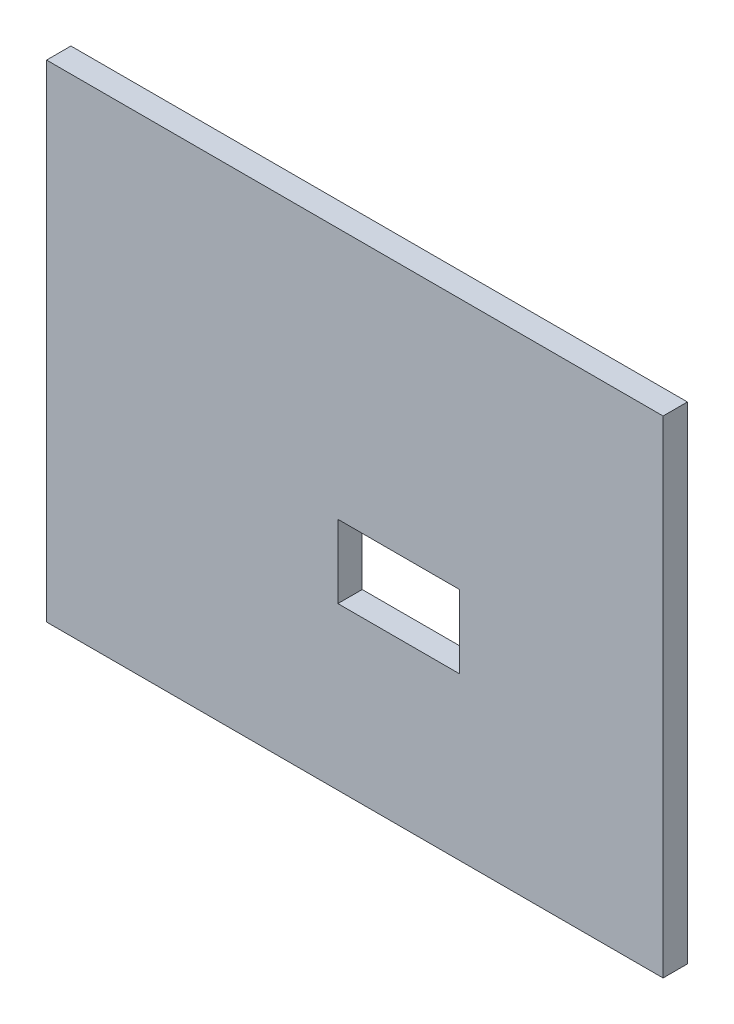
SolidWorks part; units mm, degrees
ref_plane "Front Plane" through (0, 0, 0) normal (0, 0, 1) x (1, 0, 0)
ref_plane "Top Plane" through (0, 0, 0) normal (0, 1, 0) x (1, 0, 0)
ref_plane "Right Plane" through (0, 0, 0) normal (1, 0, 0) x (0, 0, -1)
sketch "Sketch1" plane through (0, 0, 0) normal (0, 0, 1) x (1, 0, 0)
  line L1 (-38, 30) -> (38, 30)
  line L2 (-38, 30) -> (-38, -30)
  line L3 (-38, -30) -> (38, -30)
  line L4 (38, 30) -> (38, -30)
  line L5 (-38, 30) -> (38, -30) construction
  line L6 (-38, -30) -> (38, 30) construction
  point P0 (0, 0)
  dimension "D1" = 76
  dimension "D2" = 60
extrude "Boss-Extrude1" add sketch "Sketch1" along normal blind 3
sketch "Sketch2" plane through (0, 0, 3) normal (0, 0, 1) x (1, 0, 0)
  line L1 (-2.0894, -1.0713) -> (12.9106, -1.0713)
  line L2 (-2.0894, -1.0713) -> (-2.0894, -10.0713)
  line L3 (-2.0894, -10.0713) -> (12.9106, -10.0713)
  line L4 (12.9106, -1.0713) -> (12.9106, -10.0713)
  line L5 (-2.0894, -1.0713) -> (12.9106, -10.0713) construction
  line L6 (-2.0894, -10.0713) -> (12.9106, -1.0713) construction
  point P0 (5.4106, -5.5713)
  dimension "D1" = 9
  dimension "D2" = 15
extrude "Cut-Extrude1" cut sketch "Sketch2" against normal blind 3
